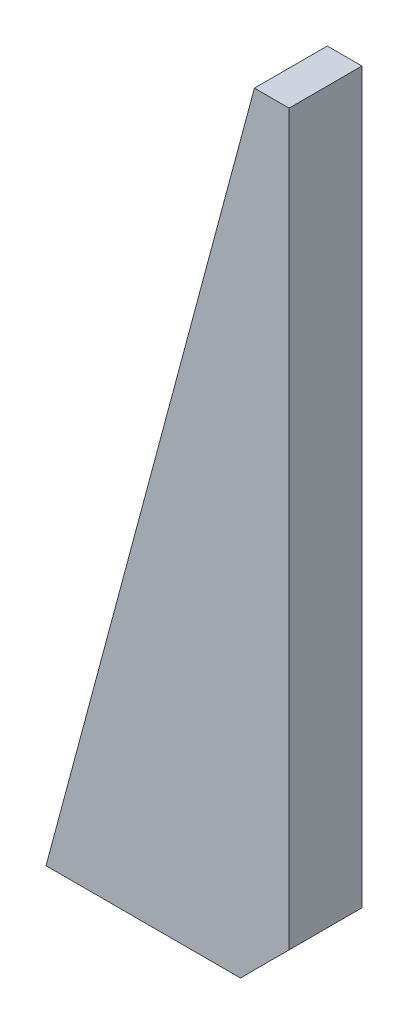
SolidWorks part; units mm, degrees
ref_plane "前基準面" through (0, 0, 0) normal (0, 0, 1) x (1, 0, 0)
ref_plane "上基準面" through (0, 0, 0) normal (0, 1, 0) x (1, 0, 0)
ref_plane "右基準面" through (0, 0, 0) normal (1, 0, 0) x (0, 0, -1)
sketch "草圖1" plane through (0, 0, 0) normal (0, 0, 1) x (1, 0, 0)
  line L0 (0, 0) -> (42.8719, 160)
  line L1 (42.8719, 160) -> (50, 160)
  line L2 (50, 160) -> (50, 10)
  line L3 (50, 10) -> (40, 0)
  line L4 (40, 0) -> (0, 0)
  point P5 (44.8548, 0)
  dimension "D1" = 160
  dimension "D2" = 50
  dimension "D3" = 75
  dimension "D4" = 45
  dimension "D5" = 10
extrude "填料-伸長1" add sketch "草圖1" along normal blind 15
